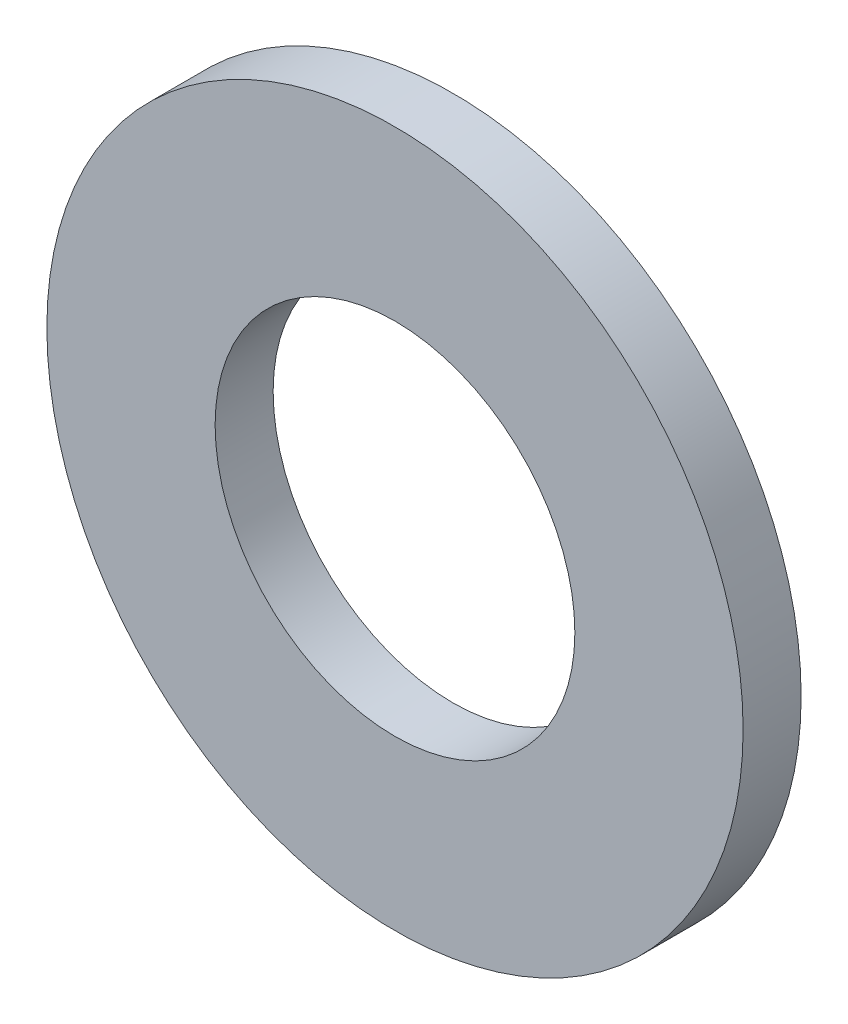
SolidWorks part; units mm, degrees
ref_plane "정면" through (0, 0, 0) normal (0, 0, 1) x (1, 0, 0)
ref_plane "윗면" through (0, 0, 0) normal (0, 1, 0) x (1, 0, 0)
ref_plane "우측면" through (0, 0, 0) normal (1, 0, 0) x (0, 0, -1)
sketch "스케치1" plane through (0, 0, 0) normal (0, 0, 1) x (1, 0, 0)
  circle A0 centre (0, 0) radius 6
  circle A1 centre (0, 0) radius 3.1
  dimension "D1" = 6.2
  dimension "D2" = 12
extrude "보스-돌출1" add sketch "스케치1" along normal blind 1
